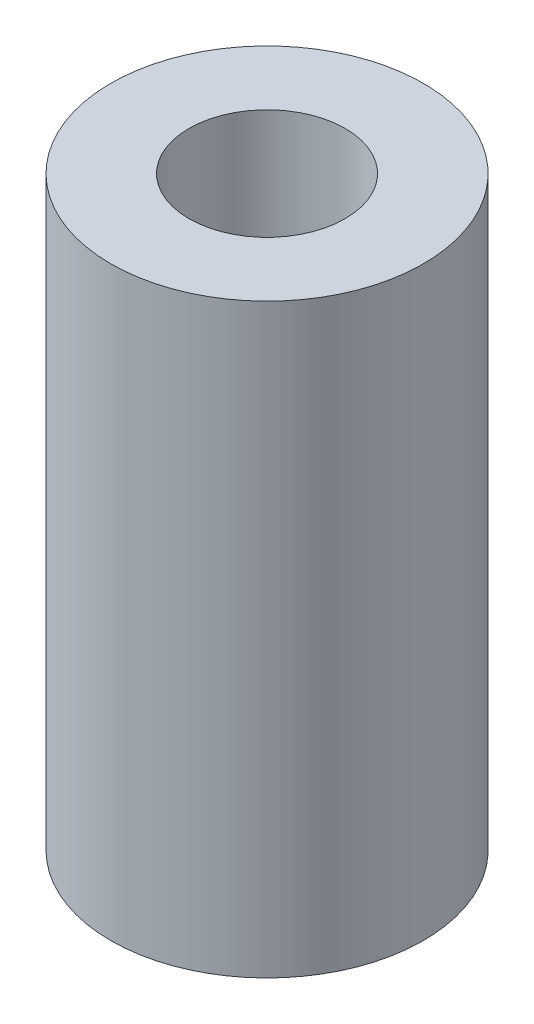
SolidWorks part; units mm, degrees
ref_plane "Front Plane" through (0, 0, 0) normal (0, 0, 1) x (1, 0, 0)
ref_plane "Top Plane" through (0, 0, 0) normal (0, 1, 0) x (1, 0, 0)
ref_plane "Right Plane" through (0, 0, 0) normal (1, 0, 0) x (0, 0, -1)
sketch "Sketch1" plane through (0, 0, 0) normal (0, 1, 0) x (1, 0, 0)
  circle A0 centre (0, 0) radius 2
  circle A1 centre (0, 0) radius 4
  dimension "D1" = 4
  dimension "D2" = 8
extrude "Boss-Extrude1" add sketch "Sketch1" along normal blind 15
